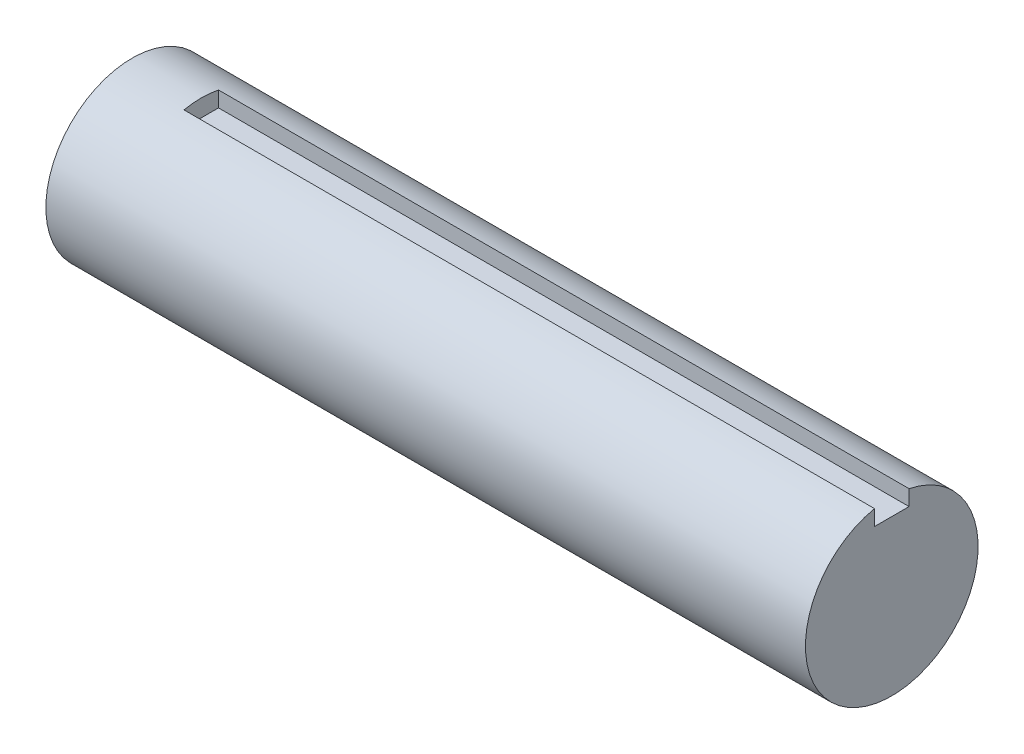
SolidWorks part; units mm, degrees
ref_plane "Front Plane" through (0, 0, 0) normal (0, 0, 1) x (1, 0, 0)
ref_plane "Top Plane" through (0, 0, 0) normal (0, 1, 0) x (1, 0, 0)
ref_plane "Right Plane" through (0, 0, 0) normal (1, 0, 0) x (0, 0, -1)
sketch "Sketch1" plane through (0, 0, 0) normal (1, 0, 0) x (0, 0, -1)
  circle A0 centre (0, 0) radius 38.1
  dimension "D1" = 76.2
extrude "Boss-Extrude1" add sketch "Sketch1" along normal blind 335.28
sketch "Sketch2" plane through (335.28, 0, 0) normal (1, 0, 0) x (0, 0, -1)
  line L0 (0, 0) -> (0, 38.1) construction
  line L2 (7.62, 45.72) -> (-7.62, 45.72)
  line L3 (7.62, 45.72) -> (7.62, 30.48)
  line L4 (7.62, 30.48) -> (-7.62, 30.48)
  line L5 (-7.62, 45.72) -> (-7.62, 30.48)
  circle A0 centre (0, 0) radius 38.1 construction
  dimension "D1" = 15.24
  dimension "D2" = 7.62
  dimension "D3" = 7.62
  dimension "D4" = 15.24
extrude "Cut-Extrude1" cut sketch "Sketch2" against normal blind 304.8
